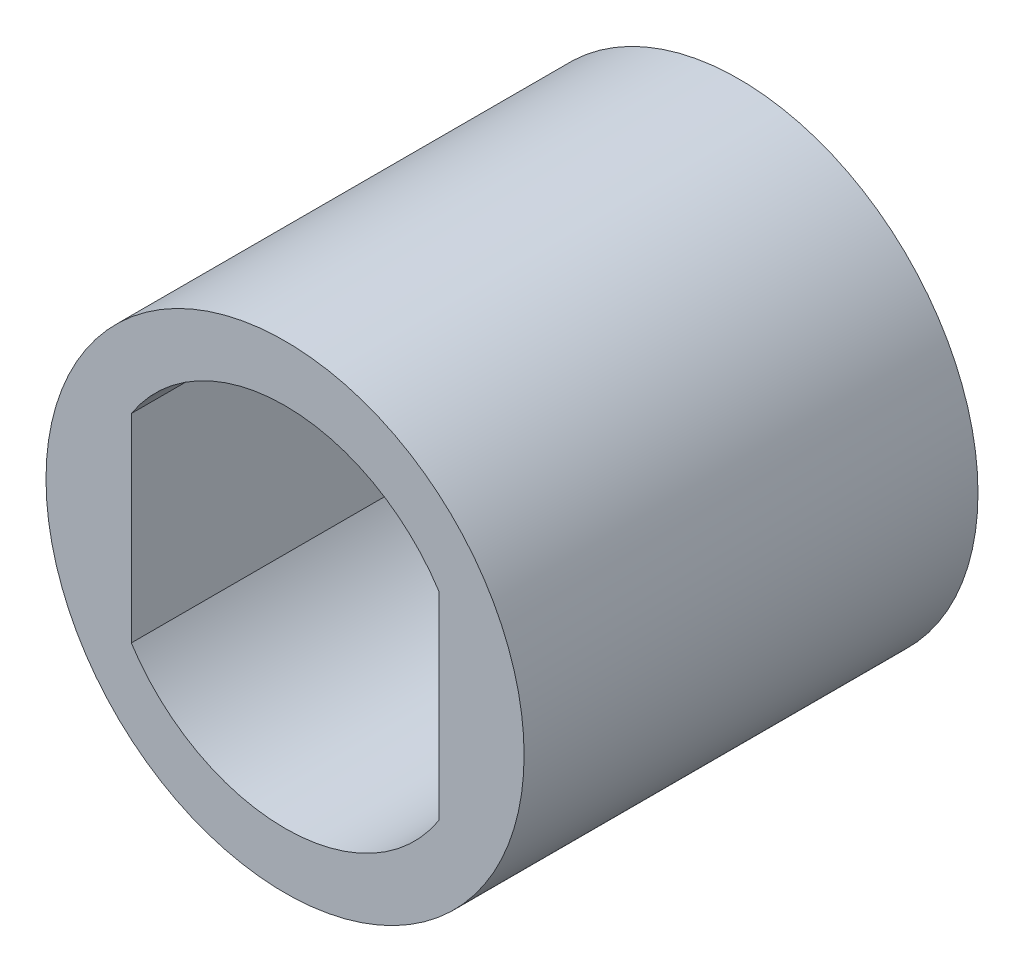
SolidWorks part; units mm, degrees
ref_plane "前视基准面" through (0, 0, 0) normal (0, 0, 1) x (1, 0, 0)
ref_plane "上视基准面" through (0, 0, 0) normal (0, 1, 0) x (1, 0, 0)
ref_plane "右视基准面" through (0, 0, 0) normal (1, 0, 0) x (0, 0, -1)
sketch "草图1" plane through (0, 0, 0) normal (0, 0, 1) x (1, 0, 0)
  line L6 (-5.082, 3.2826) -> (-5.082, -3.2826)
  line L7 (5.082, 3.2826) -> (5.082, -3.2826)
  circle A0 centre (0, 0) radius 7.9
  arc A1 (-5.082, -3.2826) -> (5.082, -3.2826) centre (0, 0) ccw
  arc A2 (5.082, 3.2826) -> (-5.082, 3.2826) centre (0, 0) ccw
extrude "凸台-拉伸1" add sketch "草图1" along normal blind 15
sketch "草图2" plane through (0, 0, 0) normal (0, 0, -1) x (-1, 0, 0)
  line L0 (0, 7.9) -> (0, -7.9) construction
  line L1 (-7.9, 0) -> (7.9, 0) construction
  circle A0 centre (0, 0) radius 7.9 construction
